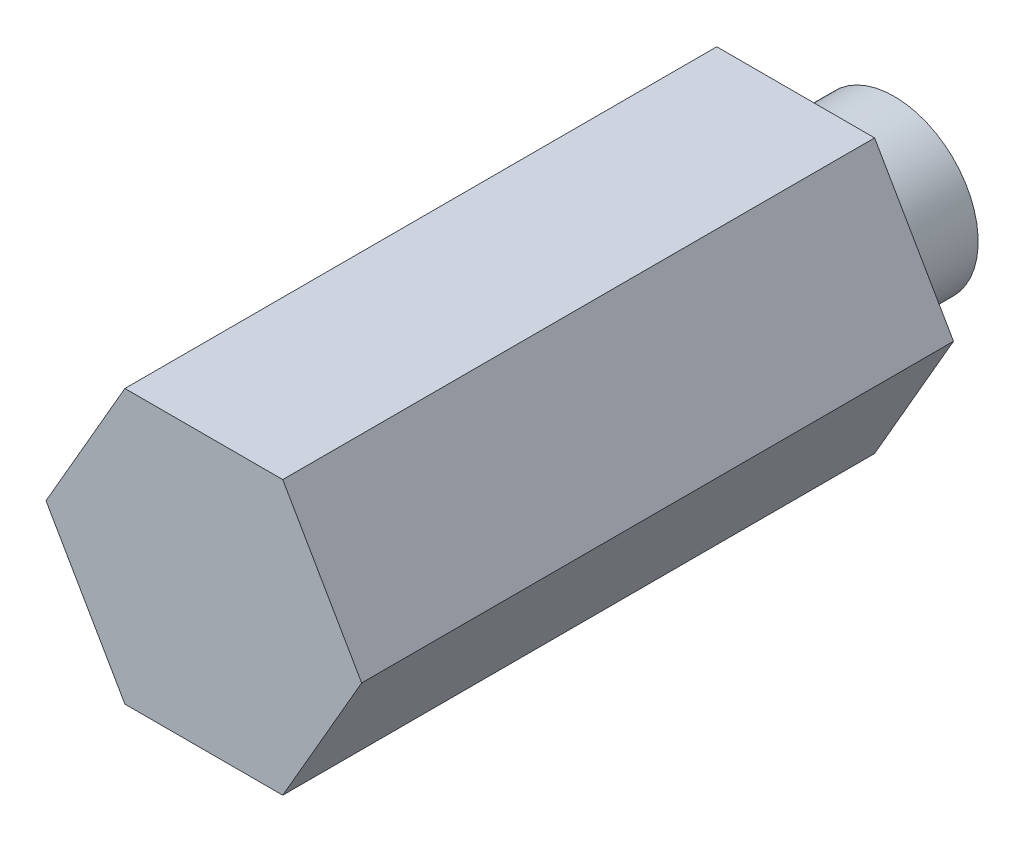
SolidWorks part; units mm, degrees
material "黄铜"
ref_plane "前视基准面" through (0, 0, 0) normal (0, 0, 1) x (1, 0, 0)
ref_plane "上视基准面" through (0, 0, 0) normal (0, 1, 0) x (1, 0, 0)
ref_plane "右视基准面" through (0, 0, 0) normal (1, 0, 0) x (0, 0, -1)
sketch "草图1" plane through (0, 0, 0) normal (0, 0, 1) x (1, 0, 0)
  line L1 (1.6, 2.7713) -> (-1.6, 2.7713)
  line L2 (-1.6, 2.7713) -> (-3.2, 0)
  line L3 (-3.2, 0) -> (-1.6, -2.7713)
  line L4 (-1.6, -2.7713) -> (1.6, -2.7713)
  line L5 (1.6, -2.7713) -> (3.2, 0)
  line L6 (3.2, 0) -> (1.6, 2.7713)
  circle A0 centre (0, 0) radius 2.7713 construction
  dimension "D1" = 3.2
extrude "凸台-拉伸1" add sketch "草图1" along normal blind 12
sketch "草图2" plane through (0, 0, 0) normal (0, 0, -1) x (-1, 0, 0)
  circle A0 centre (0, 0) radius 1.7
  dimension "D1" = 3.4
extrude "凸台-拉伸2" add sketch "草图2" along normal blind 2
